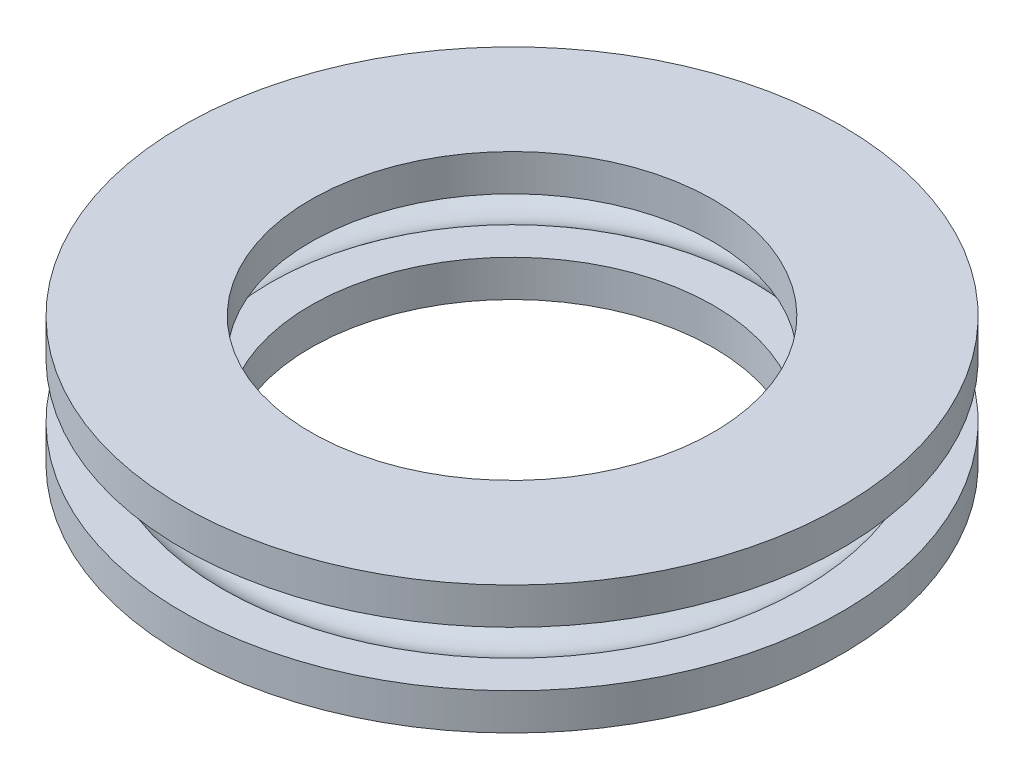
SolidWorks part; units mm, degrees
ref_plane "Front Plane" through (0, 0, 0) normal (1, 0, 0) x (0, 1, 0)
ref_plane "Top Plane" through (0, 0, 0) normal (0, 0, 1) x (0, 1, 0)
ref_plane "Right Plane" through (0, 0, 0) normal (0, 1, 0) x (-1, 0, 0)
sketch "Sketch1" plane through (0, 0, 0) normal (1, 0, 0) x (0, 1, 0)
  line L0 (0, 54.2983) -> (0, -55.438) construction
  line L1 (-72.7776, 0) -> (72.6148, 0) construction
  line L2 (-8.75, -27.5) -> (-3.75, -27.5)
  line L5 (-8.75, -45) -> (-3.75, -45)
  line L7 (-8.75, -27.5) -> (-8.75, -45)
  line L8 (-3.75, -27.5) -> (-3.75, -32.9428)
  line L9 (-3.75, -39.5572) -> (-3.75, -45)
  line L10 (3.75, -39.5572) -> (3.75, -45)
  line L11 (3.75, -27.5) -> (3.75, -32.9428)
  line L12 (8.75, -27.5) -> (8.75, -45)
  line L13 (8.75, -45) -> (3.75, -45)
  line L14 (8.75, -27.5) -> (3.75, -27.5)
  arc A0 (-3.75, -32.9428) -> (-3.75, -39.5572) centre (0, -36.25) ccw
  arc A1 (3.75, -32.9428) -> (3.75, -39.5572) centre (0, -36.25) cw
  point P15 (-8.75, -36.25)
  dimension "D4" = 10
  dimension "D1" = 5
  dimension "D2" = 17.5
  dimension "D3" = 90
  dimension "D5" = 17.5
revolve "Revolve1" add sketch "Sketch1" angle 360 about L1
